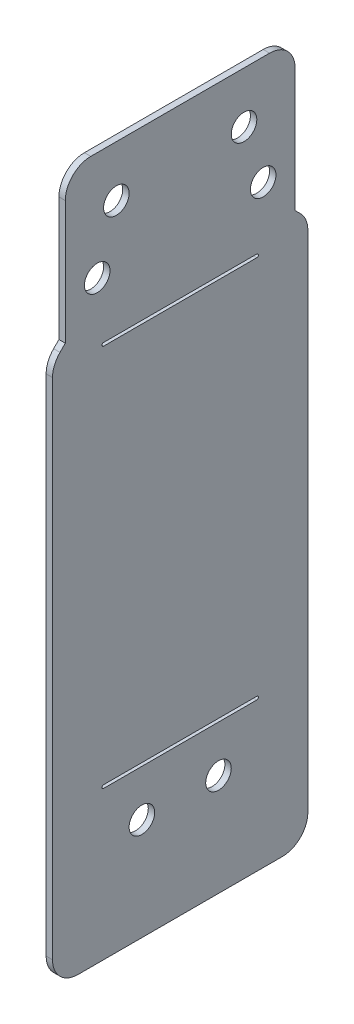
SolidWorks part; units mm, degrees
material "PVC 0.007 Plasticized"
ref_plane "Front Plane" through (0, 0, 0) normal (0, 0, 1) x (1, 0, 0)
ref_plane "Top Plane" through (0, 0, 0) normal (0, 1, 0) x (1, 0, 0)
ref_plane "Right Plane" through (0, 0, 0) normal (1, 0, 0) x (0, 0, -1)
sketch "Sketch1" plane through (0, 0, 0) normal (1, 0, 0) x (0, 0, -1)
  line L1 (-18, 0) -> (18, 0)
  line L2 (-18, 0) -> (-18, -110)
  line L3 (-18, -110) -> (18, -110)
  line L4 (18, 0) -> (18, -110)
  line L5 (-18, 0) -> (18, -110) construction
  line L6 (-18, -110) -> (18, 0) construction
  point P4 (0, -55)
  point P5 (0, 0)
  dimension "D1" = 110
  dimension "D2" = 36
extrude "Boss-Extrude1" add sketch "Sketch1" along normal blind 1 contours L2 L3 L4 L1
hole_wizard "Ø4.0 (4) Diameter Hole2" positions "Sketch2" profile "Sketch3" hole size "Ø4.0" standard "ISO" end condition through all
sketch "Sketch2" plane through (0, 0, 0) normal (-1, 0, 0) x (0, 0, 1)
  line L0 (18, 0) -> (-18, 0) construction
  line L1 (18, 0) -> (18, -110) construction
  line L2 (-18, 0) -> (-18, -110) construction
  point P0 (-10, -8)
  point P3 (10, -8)
  dimension "D1" = 8
  dimension "D2" = 8
  dimension "D3" = 8
  dimension "D4" = 8
sketch "Sketch3" plane through (0, -8, -10) normal (0, 1, 0) x (0, 0, 1)
  line L0 (0, 0) -> (0, 1)
  line L1 (0, 1) -> (2, 1)
  line L2 (2, 1) -> (2, 0)
  line L5 (2, 0) -> (0, 0)
  line L11 (0, -6.35) -> (0, 107.95) construction
  dimension "Thru Hole Dia." = 4
  dimension "Thru Hole Depth" = 1
hole_wizard "Ø4.0 (4) Diameter Hole3" positions "Sketch4" profile "Sketch5" hole size "Ø4.0" standard "ISO" end condition through all
sketch "Sketch4" plane through (0, 0, 0) normal (-1, 0, 0) x (0, 0, 1)
  line L0 (-18, 0) -> (-18, -110) construction
  line L1 (18, 0) -> (18, -110) construction
  line L2 (18, 0) -> (-18, 0) construction
  point P0 (-13, -17)
  point P3 (13, -17)
  dimension "D1" = 5
  dimension "D2" = 5
  dimension "D3" = 17
  dimension "D4" = 17
sketch "Sketch5" plane through (0, -17, -13) normal (0, 1, 0) x (0, 0, 1)
  line L0 (0, 0) -> (0, 1)
  line L1 (0, 1) -> (2, 1)
  line L2 (2, 1) -> (2, 0)
  line L5 (2, 0) -> (0, 0)
  line L11 (0, -6.35) -> (0, 107.95) construction
  dimension "Thru Hole Dia." = 4
  dimension "Thru Hole Depth" = 1
sketch "Sketch6" plane through (1, 0, 0) normal (1, 0, 0) x (0, 0, -1)
  line L0 (-18, -110) -> (18, -110) construction
  point P0 (-6, -94)
  point P1 (6, -94)
  dimension "D1" = 12
  dimension "D2" = 6
  dimension "D3" = 16
hole_wizard "Ø4.0 (4) Diameter Hole1" positions "Sketch7" profile "Sketch8" hole size "Ø4.0" standard "ISO" end condition through all
sketch "Sketch7" plane through (1, 0, 0) normal (1, 0, 0) x (0, 0, -1)
  point P0 (6, -94)
  point P3 (-6, -94)
  point P18 (0, 0)
  point P20 (0, 0)
sketch "Sketch8" plane through (1, -94, -6) normal (0, 1, 0) x (0, 0, -1)
  line L0 (0, 0) -> (0, 1)
  line L1 (0, 1) -> (2, 1)
  line L2 (2, 1) -> (2, 0)
  line L5 (2, 0) -> (0, 0)
  line L11 (0, -6.35) -> (0, 107.95) construction
  dimension "Thru Hole Dia." = 4
  dimension "Thru Hole Depth" = 1
sketch "Sketch9" plane through (0, 0, 0) normal (-1, 0, 0) x (0, 0, 1)
  line L0 (18, -23.35) -> (20, -25.35)
  line L1 (18, 0) -> (18, -110) construction
  line L2 (20, -25.35) -> (20, -110)
  line L4 (18, -110) -> (18, -23.35)
  line L5 (-18, -23.35) -> (-20, -25.35)
  line L6 (-18, 0) -> (-18, -110) construction
  line L7 (-20, -25.35) -> (-20, -110)
  line L9 (-18, -110) -> (-18, -23.35)
  line L10 (-18, -110) -> (-20, -110)
  line L11 (18, -110) -> (20, -110)
  circle A0 centre (13, -17) radius 2 construction
  circle A2 centre (-13, -17) radius 2 construction
  point P8 (20, -22.5876)
  dimension "D2" = 6.35
  dimension "D5" = 6.35
  dimension "D1" = 2
  dimension "D3" = 45
  dimension "D4" = 2
  dimension "D6" = 45
extrude "Boss-Extrude2" add sketch "Sketch9" against normal up to surface (1 mm away) up to face at (1, -94, -8)
fillet "Fillet1" radius 4 2 edges at (0.5, 0, 18) (0.5, 0, -18)
sketch "Sketch10" plane through (0, 0, 0) normal (-1, 0, 0) x (0, 0, 1)
  line L0 (12, -86.5) -> (-12, -86.5) construction
  line L1 (12, -86.75) -> (-12, -86.75)
  line L2 (12, -86.25) -> (-12, -86.25)
  line L4 (12, -26.5) -> (-12, -26.5) construction
  line L5 (12, -26.75) -> (-12, -26.75)
  line L6 (12, -26.25) -> (-12, -26.25)
  line L7 (20, -110) -> (-20, -110) construction
  arc A0 (12, -86.75) -> (12, -86.25) centre (12, -86.5) ccw
  arc A1 (-12, -86.25) -> (-12, -86.75) centre (-12, -86.5) ccw
  circle A2 centre (6, -94) radius 2 construction
  arc A3 (12, -26.75) -> (12, -26.25) centre (12, -26.5) ccw
  arc A4 (-12, -26.25) -> (-12, -26.75) centre (-12, -26.5) ccw
  point P2 (0, -86.5)
  point P7 (0, 0)
  point P14 (0, -26.5)
  point P19 (0, -110)
  dimension "D2" = 0.25
  dimension "D1" = 24
  dimension "D4" = 7.5
  dimension "D6" = 60
  dimension "D5" = 2
extrude "Cut-Extrude1" cut sketch "Sketch10" against normal through all
fillet "Fillet2" radius 4 4 edges at (0.5, -25.35, 20) (0.5, -25.35, -20) (0.5, -110, -20) (0.5, -110, 20)
